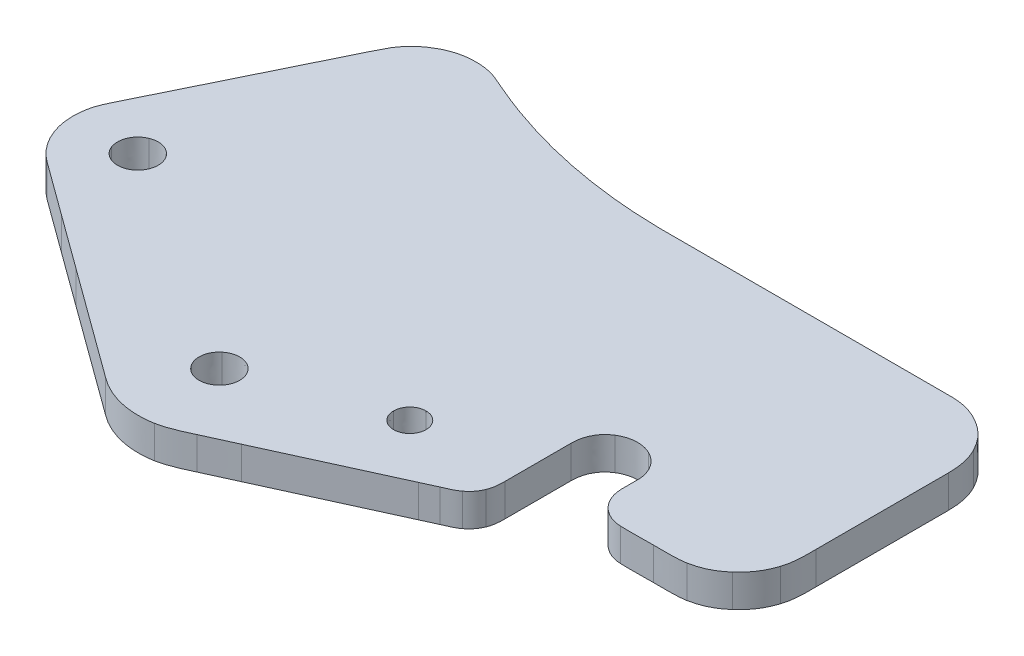
SolidWorks part; units mm, degrees
ref_plane "Front Plane" through (0, 0, 0) normal (0, 0, 1) x (1, 0, 0)
ref_plane "Top Plane" through (0, 0, 0) normal (0, 1, 0) x (1, 0, 0)
ref_plane "Right Plane" through (0, 0, 0) normal (1, 0, 0) x (0, 0, -1)
sketch "Imported Profile" plane through (0, 0, 0) normal (0, 1, 0) x (1, 0, 0)
  spline S0 degree 3 poles (47.6488, 3.4753) (40.593, 8.6202) (33.5375, 13.7602) (26.4819, 18.9072) knots 0 0 0 0 1 1 1 1
  spline S1 degree 3 poles (26.4819, 18.9072) (22.961, 21.4772) (19.4332, 24.0473) (15.9054, 26.6173) knots 0 0 0 0 1 1 1 1
  spline S2 degree 3 poles (15.9054, 26.6173) (12.3776, 29.1943) (8.8292, 31.7229) (5.329, 34.3343) knots 0 0 0 0 1 1 1 1
  spline S3 degree 3 poles (5.329, 34.3343) (1.7254, 37.0215) (-0.1832, 41.3968) (0.2923, 45.8616) knots 0 0 0 0 1 1 1 1
  spline S4 degree 3 poles (0.2923, 45.8616) (0.5679, 48.4454) (1.3534, 49.7752) (2.4489, 52.0214) knots 0 0 0 0 1 1 1 1
  spline S5 degree 3 poles (2.4489, 52.0214) (3.4066, 53.9851) (4.3713, 55.942) (5.329, 57.8988) knots 0 0 0 0 1 1 1 1
  spline S6 degree 3 poles (5.329, 57.8988) (9.1599, 65.7398) (12.9978, 73.5809) (16.8287, 81.4288) knots 0 0 0 0 1 1 1 1
  spline S7 degree 3 poles (16.8287, 81.4288) (17.2628, 82.3038) (19.1783, 86.3001) (19.7019, 87.1339) knots 0 0 0 0 1 1 1 1
  spline S8 degree 3 poles (19.7019, 87.1339) (20.9491, 89.1182) (22.4649, 90.5238) (24.532, 91.6194) knots 0 0 0 0 1 1 1 1
  spline S9 degree 3 poles (24.532, 91.6194) (26.6886, 92.7563) (28.7694, 93.2041) (31.2086, 93.0595) knots 0 0 0 0 1 1 1 1
  spline S10 degree 3 poles (31.2086, 93.0595) (33.8062, 92.9079) (34.9913, 92.2395) (37.2926, 91.2473) knots 0 0 0 0 1 1 1 1
  spline S11 degree 3 poles (37.2926, 91.2473) (45.3403, 87.754) (53.5052, 85.3975) (62.18, 84.0608) knots 0 0 0 0 1 1 1 1
  spline S12 degree 3 poles (62.18, 84.0608) (71.9503, 82.5519) (78.5373, 82.8688) (88.3283, 82.8688) knots 0 0 0 0 1 1 1 1
  spline S13 degree 3 poles (88.3283, 82.8688) (97.065, 82.8688) (105.8018, 82.8688) (114.5317, 82.8688) knots 0 0 0 0 1 1 1 1
  spline S14 degree 3 poles (114.5317, 82.8688) (118.8518, 82.8688) (123.1719, 82.8688) (127.499, 82.8688) knots 0 0 0 0 1 1 1 1
  spline S15 degree 3 poles (127.499, 82.8688) (129.6487, 82.8688) (131.7985, 82.9378) (133.9413, 82.8638) knots 0 0 0 0 1 1 1 1
  spline S16 degree 3 poles (133.9413, 82.8638) (136.2426, 82.7813) (138.1926, 82.1886) (140.1494, 80.9759) knots 0 0 0 0 1 1 1 1
  spline S17 degree 3 poles (140.1494, 80.9759) (142.244, 79.6874) (143.6978, 78.1096) (144.8071, 75.9116) knots 0 0 0 0 1 1 1 1
  spline S18 degree 3 poles (144.8071, 75.9116) (145.8338, 73.8928) (146.1783, 71.8946) (146.1783, 69.6692) knots 0 0 0 0 1 1 1 1
  spline S19 degree 3 poles (146.1783, 69.6692) (146.1783, 65.3489) (146.1783, 61.022) (146.1783, 56.7017) knots 0 0 0 0 1 1 1 1
  spline S20 degree 3 poles (146.1783, 56.7017) (146.1783, 52.3954) (146.1783, 48.089) (146.1783, 43.7827) knots 0 0 0 0 1 1 1 1
  spline S21 degree 3 poles (146.1783, 43.7827) (146.1783, 41.6536) (146.2543, 39.5865) (145.5788, 37.485) knots 0 0 0 0 1 1 1 1
  spline S22 degree 3 poles (145.5788, 37.485) (144.8416, 35.1768) (143.6909, 33.4061) (141.865, 31.8006) knots 0 0 0 0 1 1 1 1
  spline S23 degree 3 poles (141.865, 31.8006) (140.0805, 30.2296) (138.2063, 29.3133) (135.8637, 28.8654) knots 0 0 0 0 1 1 1 1
  spline S24 degree 3 poles (135.8637, 28.8654) (134.2514, 28.5624) (131.137, 28.6449) (129.5247, 28.6449) knots 0 0 0 0 1 1 1 1
  spline S25 degree 3 poles (129.5247, 28.6449) (127.3818, 28.6449) (125.2321, 28.5624) (123.0893, 28.6449) knots 0 0 0 0 1 1 1 1
  spline S26 degree 3 poles (123.0893, 28.6449) (120.7879, 28.7344) (118.714, 30.0574) (117.6736, 32.1107) knots 0 0 0 0 1 1 1 1
  spline S27 degree 3 poles (117.6736, 32.1107) (116.5849, 34.2328) (117.0741, 36.3137) (116.9708, 38.4427) knots 0 0 0 0 1 1 1 1
  spline S28 degree 3 poles (116.9708, 38.4427) (116.8538, 40.751) (115.5032, 42.8042) (113.4292, 43.824) knots 0 0 0 0 1 1 1 1
  spline S29 degree 3 poles (113.4292, 43.824) (111.4448, 44.8024) (109.1022, 44.6715) (107.2349, 43.4935) knots 0 0 0 0 1 1 1 1
  spline S30 degree 3 poles (107.2349, 43.4935) (105.1885, 42.1981) (104.279, 40.1655) (104.279, 37.8228) knots 0 0 0 0 1 1 1 1
  spline S31 degree 3 poles (104.279, 37.8228) (104.279, 33.5096) (104.279, 29.1963) (104.279, 24.8762) knots 0 0 0 0 1 1 1 1
  spline S32 degree 3 poles (104.279, 24.8762) (104.279, 23.7806) (104.224, 22.7471) (103.79, 21.6998) knots 0 0 0 0 1 1 1 1
  spline S33 degree 3 poles (103.79, 21.6998) (103.335, 20.618) (102.7014, 19.7981) (101.7643, 19.0884) knots 0 0 0 0 1 1 1 1
  spline S34 degree 3 poles (101.7643, 19.0884) (100.8824, 18.4201) (99.8833, 18.0618) (98.9049, 17.6208) knots 0 0 0 0 1 1 1 1
  spline S35 degree 3 poles (98.9049, 17.6208) (97.9265, 17.1728) (96.9481, 16.7251) (95.9628, 16.2772) knots 0 0 0 0 1 1 1 1
  spline S36 degree 3 poles (95.9628, 16.2772) (88.046, 12.6668) (80.1291, 9.0563) (72.2054, 5.4458) knots 0 0 0 0 1 1 1 1
  spline S37 degree 3 poles (72.2054, 5.4458) (70.2279, 4.5501) (68.2504, 3.6475) (66.2729, 2.7449) knots 0 0 0 0 1 1 1 1
  spline S38 degree 3 poles (66.2729, 2.7449) (64.2955, 1.8423) (62.3869, 0.8983) (60.2027, 0.4918) knots 0 0 0 0 1 1 1 1
  spline S39 degree 3 poles (60.2027, 0.4918) (55.7792, -0.335) (51.2248, 0.7468) (47.6488, 3.4753) knots 0 0 0 0 1 1 1 1
  spline S40 degree 3 poles (87.8115, 25.9559) (87.8115, 27.706) (86.3921, 29.1253) (84.6351, 29.1253) knots 0 0 0 0 1 1 1 1
  spline S41 degree 3 poles (84.6351, 29.1253) (82.8781, 29.1253) (81.4587, 27.706) (81.4587, 25.9559) knots 0 0 0 0 1 1 1 1
  spline S42 degree 3 poles (81.4587, 25.9559) (81.4587, 24.1988) (82.8781, 22.7795) (84.6351, 22.7795) knots 0 0 0 0 1 1 1 1
  spline S43 degree 3 poles (84.6351, 22.7795) (86.3921, 22.7795) (87.8115, 24.1988) (87.8115, 25.9559) knots 0 0 0 0 1 1 1 1
  spline S44 degree 3 poles (16.5876, 46.0339) (15.747, 48.0596) (13.425, 49.0242) (11.3993, 48.1836) knots 0 0 0 0 1 1 1 1
  spline S45 degree 3 poles (11.3993, 48.1836) (9.3735, 47.343) (8.4158, 45.021) (9.2495, 42.9953) knots 0 0 0 0 1 1 1 1
  spline S46 degree 3 poles (9.2495, 42.9953) (10.0901, 40.9696) (12.4121, 40.0118) (14.4378, 40.8455) knots 0 0 0 0 1 1 1 1
  spline S47 degree 3 poles (14.4378, 40.8455) (16.4635, 41.6862) (17.4213, 44.0081) (16.5876, 46.0339) knots 0 0 0 0 1 1 1 1
  spline S48 degree 3 poles (60.32, 18.6385) (58.914, 20.3197) (56.4129, 20.5402) (54.7317, 19.1275) knots 0 0 0 0 1 1 1 1
  spline S49 degree 3 poles (54.7317, 19.1275) (53.0505, 17.7219) (52.83, 15.2207) (54.2427, 13.5395) knots 0 0 0 0 1 1 1 1
  spline S50 degree 3 poles (54.2427, 13.5395) (55.6552, 11.8583) (58.1563, 11.6447) (59.8375, 13.0505) knots 0 0 0 0 1 1 1 1
  spline S51 degree 3 poles (59.8375, 13.0505) (61.5118, 14.4561) (61.7323, 16.9642) (60.32, 18.6385) knots 0 0 0 0 1 1 1 1
extrude "Boss-Extrude1" add sketch "Imported Profile" along normal blind 6.35
sketch "Sketch1" plane through (0, 6.35, 0) normal (0, 1, 0) x (1, 0, 0)
  circle A1 centre (77.6778, 184.4719) radius 101.6
  spline S2 degree 3 poles (88.3283, 82.8688) (78.5373, 82.8688) (71.9503, 82.5519) (62.18, 84.0608) knots 0 0 0 0 1 1 1 1 construction
  point P2 (74.8604, 196.2)
  point P5 (88.3279, 184.4688)
  dimension "D1" = 203.2
sketch "Sketch2" plane through (0, 6.35, 0) normal (0, 1, 0) x (1, 0, 0)
  circle A1 centre (84.6351, 25.9559) radius 3.1764
  circle A2 centre (57.2811, 16.0861) radius 3.9686
  circle A3 centre (12.9185, 44.5146) radius 3.9712
